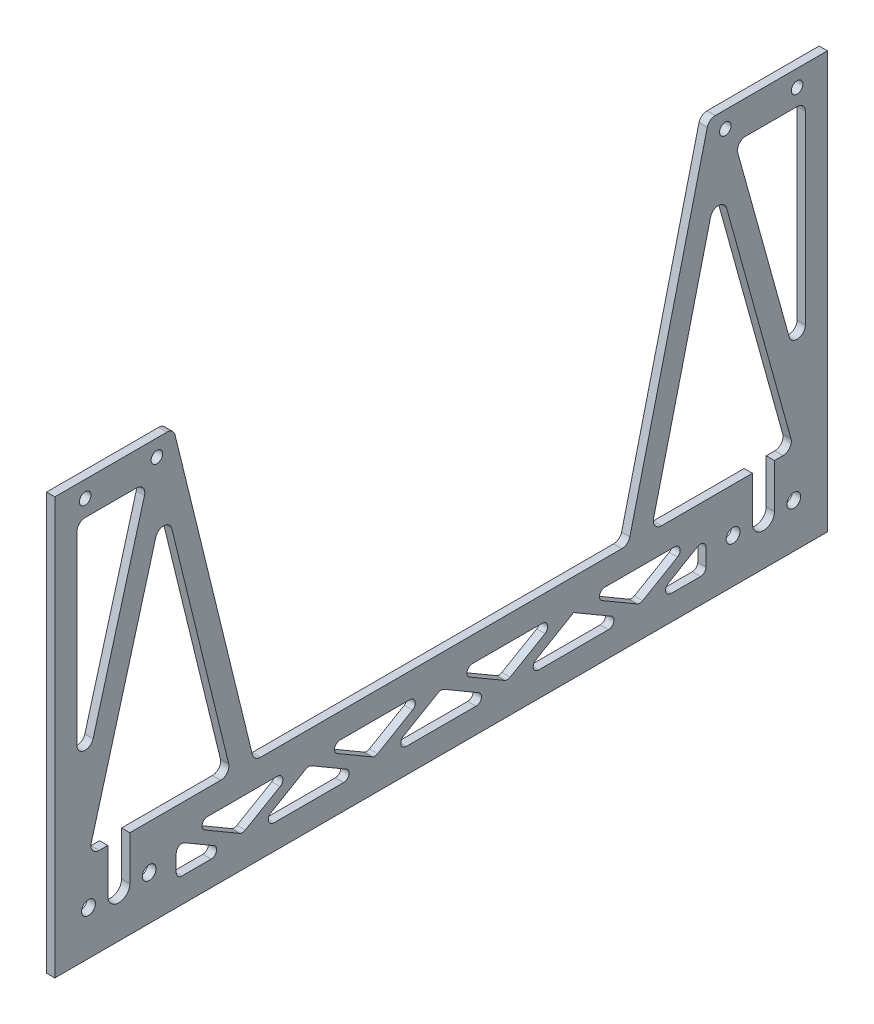
SolidWorks part; units mm, degrees
material "Thornel Mat VMA"
ref_plane "Front Plane" through (0, 0, 0) normal (0, 0, 1) x (1, 0, 0)
ref_plane "Top Plane" through (0, 0, 0) normal (0, 1, 0) x (1, 0, 0)
ref_plane "Right Plane" through (0, 0, 0) normal (1, 0, 0) x (0, 0, -1)
sketch "Sketch1" plane through (0, 0, 0) normal (1, 0, 0) x (0, 0, -1)
  line L0 (0, 0) -> (0, 75.5)
  line L2 (21.5, 75.5) -> (40, 0)
  line L3 (40, 0) -> (35.8817, 0)
  line L4 (35.8817, 0) -> (29.7558, 25)
  line L5 (29.7558, 25) -> (4, 25)
  line L6 (4, 25) -> (4, 0)
  line L7 (4, 0) -> (0, 0)
  line L8 (4, 69.5) -> (18.8519, 69.5)
  line L9 (18.8519, 69.5) -> (4, 29)
  line L10 (4, 29) -> (4, 69.5)
  line L11 (8.2605, 29) -> (20.5584, 62.5355)
  line L12 (20.5584, 62.5355) -> (28.7757, 29)
  line L13 (28.7757, 29) -> (8.2605, 29)
  line L15 (21.5, 75.5) -> (0, 75.5)
  circle A0 centre (5.5, 72.5) radius 1.05
  circle A1 centre (18.5, 72.5) radius 1.05
  dimension "D4" = 2.1
  dimension "D1" = 4
  dimension "D2" = 4
  dimension "D3" = 25
  dimension "D5" = 72.5
  dimension "D6" = 40
  dimension "D8" = 13
  dimension "D9" = 5.5
  dimension "D10" = 3
  dimension "D11" = 4
  dimension "D12" = 3
  dimension "D13" = 4
  dimension "D7" = 3
extrude "Boss-Extrude1" add sketch "Sketch1" along normal blind 1.5
fillet "Fillet1" radius 1.5 9 edges at (0.75, 29, -4) (0.75, 29, -8.2605) (0.75, 25, -29.7558) (0.75, 25, -4) (0.75, 69.5, -4) (0.75, 69.5, -18.8519) (0.75, 62.5355, -20.5584) (0.75, 29, -28.7757) (0.75, 75.5, -21.5)
sketch "Sketch2" plane through (1.5, 0, 0) normal (1, 0, 0) x (0, 0, -1)
  line L0 (70, 16) -> (70, 0) construction
  line L3 (0, 16) -> (103.9205, 16)
  line L14 (109.9641, 23.857) -> (108.0389, 16)
  line L15 (134.5, 25) -> (111.421, 25)
  line L16 (136, 16) -> (136, 23.5)
  line L18 (140, 75.5) -> (140, 0)
  line L19 (119.6768, 75.5) -> (140, 75.5)
  line L20 (103.9205, 16) -> (118.2199, 74.357)
  line L37 (140, 0) -> (140, 16)
  line L195 (108.0389, 16) -> (136, 16)
  line L197 (0, 16) -> (0, 0)
  line L208 (140, 0) -> (0, 0)
  line L212 (129.5918, 29) -> (113.1362, 29)
  line L215 (121.1357, 57.9158) -> (131.0001, 31.0164)
  line L216 (111.6793, 30.857) -> (118.2705, 57.7563)
  line L217 (123.2959, 69.5) -> (134.5, 69.5)
  line L218 (136, 68) -> (136, 37.4472)
  line L219 (133.0917, 36.9307) -> (121.8876, 67.4836)
  arc A3 (109.9641, 23.857) -> (111.421, 25) centre (111.421, 23.5) cw
  arc A4 (134.5, 25) -> (136, 23.5) centre (134.5, 23.5) cw
  arc A5 (118.2199, 74.357) -> (119.6768, 75.5) centre (119.6768, 74) cw
  arc A261 (131.0001, 31.0164) -> (129.5918, 29) centre (129.5918, 30.5) cw
  arc A268 (118.2705, 57.7563) -> (121.1357, 57.9158) centre (119.7274, 57.3993) cw
  arc A269 (113.1362, 29) -> (111.6793, 30.857) centre (113.1362, 30.5) cw
  arc A270 (134.5, 69.5) -> (136, 68) centre (134.5, 68) cw
  arc A271 (121.8876, 67.4836) -> (123.2959, 69.5) centre (123.2959, 68) cw
  arc A272 (136, 37.4472) -> (133.0917, 36.9307) centre (134.5, 37.4472) cw
  circle A273 centre (121.5, 72.5) radius 1.05
  circle A274 centre (134.5, 72.5) radius 1.05
  line M36 (40, 0) -> (21.7801, 74.357)
  line M39 (0, 75.5) -> (0, 0)
  line M40 (0, 0) -> (4, 0)
  line M41 (4, 0) -> (4, 23.5)
  line M45 (30.0359, 23.857) -> (35.8817, 0)
  line M46 (35.8817, 0) -> (40, 0)
extrude "Boss-Extrude2" add sketch "Sketch2" against normal up to surface (1.5 mm away) contours L0 L3 L208 M36 | L3 L0 L208 L18 L19 A5 L20 A273 L15 A4 L16 L195 L14 A3 L212 A269 L216 A268 L215 A261 L218 A272 L219 A271 L217 A270 A274 | L208 L3 M45 M41 | L3 M45 M46 M36 | L3 M39 M40 M41 up to face at (0, 72.5, -6.55)
sketch "Sketch4" plane through (1.5, 0, 0) normal (1, 0, 0) x (0, 0, -1)
  line L0 (70, 16) -> (70, 0) construction
  line L1 (36.0795, 16) -> (103.9205, 16) construction
  line L2 (0, 0) -> (140, 0) construction
  line L3 (6.1, 8) -> (11.6, 8) construction
  line L4 (11.6, 8) -> (17.1, 8) construction
  line L5 (0, 75.5) -> (0, 0) construction
  line L12 (130.4, 16) -> (130.4, 8)
  line L13 (126.4, 8) -> (126.4, 16)
  line L14 (13.6, 16) -> (13.6, 8)
  line L15 (9.6, 8) -> (9.6, 16)
  line L16 (126.4, 16) -> (130.4, 16)
  line L17 (9.6, 16) -> (13.6, 16)
  circle A0 centre (6.1, 8) radius 1.25
  circle A1 centre (17.1, 8) radius 1.25
  circle A3 centre (122.9, 8) radius 1.25
  circle A5 centre (133.9, 8) radius 1.25
  arc A6 (126.4, 8) -> (130.4, 8) centre (128.4, 8) ccw
  arc A7 (13.6, 8) -> (9.6, 8) centre (11.6, 8) cw
  dimension "D1" = 6.1
  dimension "D3" = 2.5
  dimension "D4" = 11
  dimension "D5" = 8
extrude "Cut-Extrude2" cut sketch "Sketch4" against normal through all
sketch "Sketch5" plane through (1.5, 0, 0) normal (1, 0, 0) x (0, 0, -1)
  line L0 (35.9846, 4.5) -> (46, 4.5)
  line L5 (47.9846, 11.5) -> (68.0154, 11.5)
  line L6 (59.9846, 4.5) -> (70, 4.5)
  line L17 (22, 4.5) -> (22, 10.3423)
  line L18 (23.9846, 11.5) -> (44.0154, 11.5)
  line L19 (118, 4.5) -> (118, 10.3423)
  line L21 (22, 4.5) -> (32.0154, 4.5)
  line L22 (46, 4.5) -> (56.0154, 4.5)
  line L24 (70, 4.5) -> (80.0154, 4.5)
  line L25 (94, 4.5) -> (104.0154, 4.5)
  line L26 (107.9846, 4.5) -> (118, 10.3423)
  line L27 (107.9846, 4.5) -> (118, 4.5)
  line L28 (83.9846, 4.5) -> (94, 4.5)
  line L29 (95.9846, 11.5) -> (116.0154, 11.5)
  line L30 (71.9846, 11.5) -> (92.0154, 11.5)
  line L34 (32.0154, 4.5) -> (22, 10.3423)
  line L35 (35.9846, 4.5) -> (46, 10.3423)
  line L36 (46, 10.3423) -> (56.0154, 4.5)
  line L37 (59.9846, 4.5) -> (70, 10.3423)
  line L38 (70, 10.3423) -> (80.0154, 4.5)
  line L39 (83.9846, 4.5) -> (94, 10.3423)
  line L40 (94, 10.3423) -> (104.0154, 4.5)
  line L42 (34, 5.6577) -> (23.9846, 11.5)
  line L43 (34, 5.6577) -> (44.0154, 11.5)
  line L44 (47.9846, 11.5) -> (58, 5.6577)
  line L45 (58, 5.6577) -> (68.0154, 11.5)
  line L46 (71.9846, 11.5) -> (82, 5.6577)
  line L47 (82, 5.6577) -> (92.0154, 11.5)
  line L48 (95.9846, 11.5) -> (106, 5.6577)
  line L49 (106, 5.6577) -> (116.0154, 11.5)
  point P4 (46, 4.5)
  point P6 (22, 4.5)
  point P7 (118, 11.5)
  point P8 (94, 4.5)
  point P10 (70, 4.5)
extrude "Cut-Extrude4" cut sketch "Sketch5" against normal through all
fillet "Fillet3" radius 1 26 edges at (0.75, 11.5, -95.9846) (0.75, 11.5, -116.0154) (0.75, 10.3423, -118) (0.75, 4.5, -107.9846) (0.75, 4.5, -118) (0.75, 4.5, -104.0154) (0.75, 4.5, -83.9846) (0.75, 11.5, -92.0154) (0.75, 11.5, -71.9846) (0.75, 5.6577, -106) (0.75, 5.6577, -82) (0.75, 4.5, -80.0154) (0.75, 4.5, -59.9846) (0.75, 10.3423, -70) (0.75, 11.5, -68.0154) (0.75, 11.5, -47.9846) (0.75, 5.6577, -58) (0.75, 4.5, -56.0154) (0.75, 10.3423, -46) (0.75, 4.5, -35.9846) (0.75, 5.6577, -34) (0.75, 11.5, -44.0154) (0.75, 4.5, -32.0154) (0.75, 4.5, -22) (0.75, 10.3423, -22) (0.75, 11.5, -23.9846)
sketch "Sketch6" plane through (1.5, 0, 0) normal (1, 0, 0) x (0, 0, -1)
  line L2 (4, 16) -> (4, 23.5) construction
  line L3 (4, 19.75) -> (30.9985, 19.9285)
  line L4 (30.0359, 23.857) -> (31.9611, 16) construction
  line L5 (30.9985, 19.9285) -> (18.8519, 69.5)
  line L7 (18.8519, 69.5) -> (4, 69.5)
  line L8 (4, 69.5) -> (4, 19.75)
  line L9 (70, 16) -> (70, 0) construction
  line L11 (0, 0) -> (140, 0) construction
  line L12 (136, 69.5) -> (136, 19.75)
  line L13 (121.1481, 69.5) -> (136, 69.5)
  line L14 (109.0015, 19.9285) -> (121.1481, 69.5)
  line L15 (136, 19.75) -> (109.0015, 19.9285)
extrude "Cut-Extrude5" cut sketch "Sketch6" against normal through all
sketch "Sketch7" plane through (1.5, 0, 0) normal (1, 0, 0) x (0, 0, -1)
  line L0 (18.8519, 69.5) -> (16.7762, 69.5)
  line L1 (18.8519, 69.5) -> (19.825, 65.5285)
  line L2 (6.0756, 16) -> (19.825, 65.5285)
  line L3 (136, 16) -> (136, 23.4769)
  line L4 (4, 23.4769) -> (16.7762, 69.5)
  line L5 (136, 16) -> (133.9244, 16)
  line L6 (18.8519, 69.5) -> (31.9611, 16) construction
  line L7 (4, 16) -> (6.0756, 16)
  line L8 (4, 16) -> (9.6, 16) construction
  line L9 (4, 16) -> (4, 23.4769)
  line L10 (4, 69.5) -> (4, 16) construction
  line L11 (70, 16) -> (70, 0) construction
  line L12 (36.0795, 16) -> (103.9205, 16) construction
  line L13 (0, 0) -> (140, 0) construction
  line L14 (136, 23.4769) -> (123.2238, 69.5)
  line L15 (133.9244, 16) -> (120.175, 65.5285)
  line L16 (121.1481, 69.5) -> (120.175, 65.5285)
  line L17 (121.1481, 69.5) -> (123.2238, 69.5)
extrude "Boss-Extrude3" add sketch "Sketch7" against normal up to surface (1.5 mm away) up to face at (0, 27.125, -13.1516)
fillet "Fillet4" radius 1.5 14 edges at (0.75, 16, -103.9205) (0.75, 16, -36.0795) (0.75, 16, -31.9611) (0.75, 65.5285, -19.825) (0.75, 69.5, -16.7762) (0.75, 69.5, -4) (0.75, 69.5, -136) (0.75, 69.5, -123.2238) (0.75, 65.5285, -120.175) (0.75, 16, -133.9244) (0.75, 23.4769, -136) (0.75, 23.4769, -4) (0.75, 16, -108.0389) (0.75, 16, -6.0756)
sketch "Sketch3" plane through (1.5, 0, 0) normal (1, 0, 0) x (0, 0, -1)
  line L0 (70, 16) -> (70, 0) construction
  line L1 (0, 0) -> (8, 0)
  line L2 (0, 0) -> (0, 8)
  line L3 (0, 8) -> (8, 8)
  line L4 (8, 0) -> (8, 8)
  line L5 (36.0795, 16) -> (103.9205, 16) construction
  line L6 (0, 0) -> (140, 0) construction
  line L7 (140, 8) -> (132, 8)
  line L8 (132, 0) -> (132, 8)
  line L9 (140, 0) -> (132, 0)
  line L10 (140, 0) -> (140, 8)
  dimension "D1" = 8
equation "\"D2@Sketch1\"=\"D1@Sketch1\""
equation "\"D10@Sketch1\"=\"D7@Sketch1\""
equation "\"D11@Sketch1\"=\"D1@Sketch1\""
equation "\"D12@Sketch1\"=\"D7@Sketch1\""
equation "\"D13@Sketch1\"=\"D1@Sketch1\""
